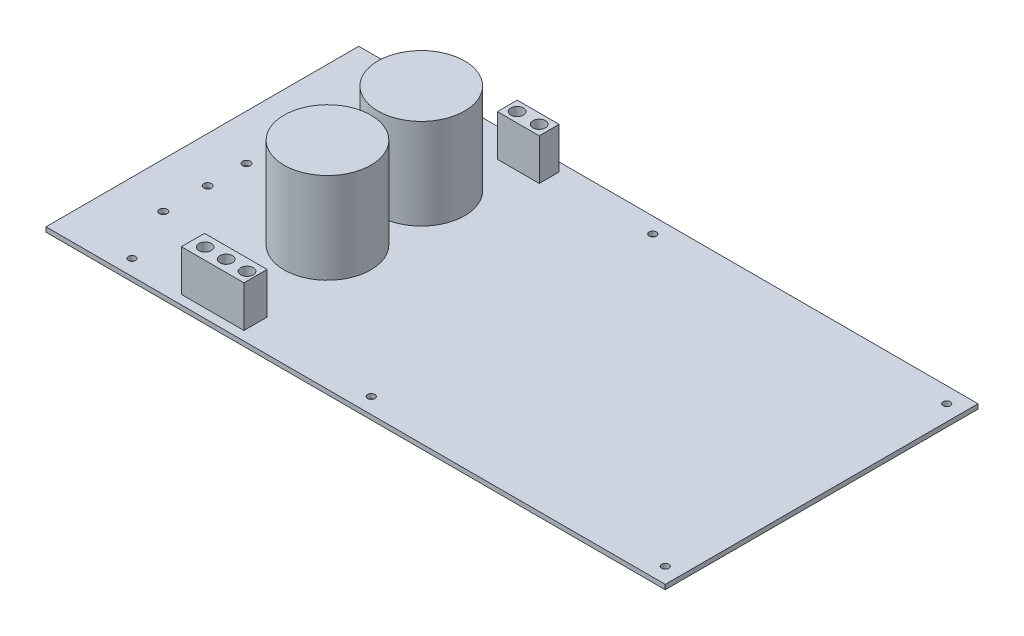
SolidWorks part; units mm, degrees
ref_plane "Front Plane" through (0, 0, 0) normal (0, 0, 1) x (1, 0, 0)
ref_plane "Top Plane" through (0, 0, 0) normal (0, 1, 0) x (1, 0, 0)
ref_plane "Right Plane" through (0, 0, 0) normal (1, 0, 0) x (0, 0, -1)
sketch "Sketch1" plane through (0, 0, 0) normal (0, 1, 0) x (1, 0, 0)
  line L0 (18.415, -36.8184) -> (18.415, -91.2497) construction
  line L1 (0, 0) -> (251.46, 0)
  line L2 (0, 0) -> (0, -127)
  line L3 (0, -127) -> (251.46, -127)
  line L4 (251.46, 0) -> (251.46, -127)
  circle A0 centre (28.575, -120.65) radius 1.4605
  circle A1 centre (28.575, -6.35) radius 1.4605
  circle A2 centre (245.11, -6.35) radius 1.4605
  circle A3 centre (245.11, -120.65) radius 1.4605
  circle A4 centre (125.73, -6.35) radius 1.4605
  circle A5 centre (125.73, -120.65) radius 1.4605
  circle A6 centre (18.415, -44.45) radius 1.5875
  circle A7 centre (18.415, -79.756) radius 1.5875
  circle A8 centre (18.415, -64.0341) radius 1.5875
  circle A9 centre (18.415, -97.79) radius 1.5875
  dimension "D3" = 2.921
  dimension "D6" = 6.35
  dimension "D7" = 6.35
  dimension "D8" = 119.38
  dimension "D11" = 114.3
  dimension "D12" = 114.3
  dimension "D13" = 6.35
  dimension "D14" = 3.175
  dimension "D1" = 251.46
  dimension "D2" = 127
  dimension "D4" = 28.575
  dimension "D5" = 28.575
  dimension "D9" = 119.38
  dimension "D10" = 114.3
  dimension "D15" = 18.415
  dimension "D16" = 53.34
  dimension "D17" = 44.45
extrude "Extrude1" add sketch "Sketch1" against normal blind 1.905
sketch "Sketch2" plane through (0, 0, 0) normal (0, 1, 0) x (1, 0, 0)
  circle A0 centre (63.5, -76.2) radius 17.6213
  circle A1 centre (63.5, -38.1) radius 17.6213
  dimension "D1" = 35.2425
  dimension "D3" = 38.1
  dimension "D5" = 38.1
  dimension "D4" = 63.5
  dimension "D2" = 63.5
extrude "Extrude2" add sketch "Sketch2" along normal blind 36.83
sketch "Sketch3" plane through (0, 0, 0) normal (0, 1, 0) x (1, 0, 0)
  line L1 (51.2501, -123.2705) -> (76.6501, -123.2705)
  line L2 (51.2501, -123.2705) -> (51.2501, -113.8725)
  line L3 (51.2501, -113.8725) -> (76.6501, -113.8725)
  line L4 (76.6501, -123.2705) -> (76.6501, -113.8725)
  line L5 (67.8875, -11.6086) -> (84.9055, -11.6086)
  line L6 (67.8875, -11.6086) -> (67.8875, -3.5369)
  line L7 (67.8875, -3.5369) -> (84.9055, -3.5369)
  line L8 (84.9055, -11.6086) -> (84.9055, -3.5369)
  circle A0 centre (56.1955, -118.5849) radius 2.54
  circle A1 centre (64.7415, -118.5849) radius 2.54
  circle A2 centre (73.2196, -118.5849) radius 2.54
  circle A3 centre (71.8653, -7.5728) radius 2.54
  circle A4 centre (80.8361, -7.5728) radius 2.54
  dimension "D1" = 5.08
  dimension "D4" = 5.08
  dimension "D2" = 25.4
  dimension "D3" = 9.398
  dimension "D5" = 17.018
extrude "Extrude3" add sketch "Sketch3" along normal blind 16.764
sketch "Sketch4" plane through (0, 0, 0) normal (0, 1, 0) x (-1, 0, 0)
  text T0 "Power in" font "Century Gothic" height in points 20
  text T1 "To cryocooler" font "Century Gothic" height in points 18
